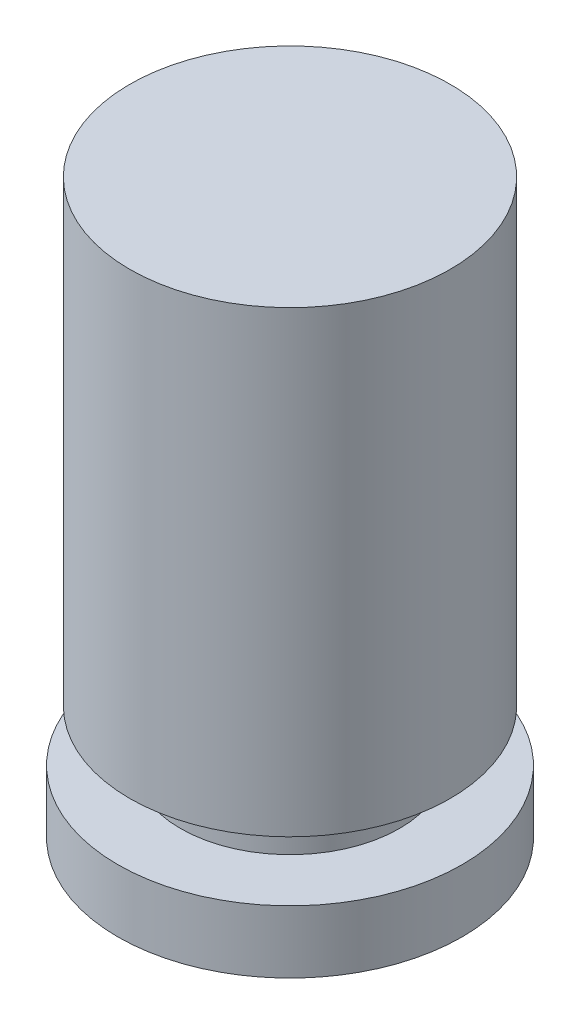
SolidWorks part; units mm, degrees
ref_plane "Front Plane" through (0, 0, 0) normal (0, 0, 1) x (1, 0, 0)
ref_plane "Top Plane" through (0, 0, 0) normal (0, 1, 0) x (1, 0, 0)
ref_plane "Right Plane" through (0, 0, 0) normal (1, 0, 0) x (0, 0, -1)
sketch "Sketch1" plane through (0, 0, 0) normal (0, 1, 0) x (1, 0, 0)
  circle A0 centre (0, 0) radius 34.925
extrude "Boss-Extrude1" add sketch "Sketch1" along normal blind 12.7
sketch "Sketch2" plane through (0, 12.7, 0) normal (0, 1, 0) x (1, 0, 0)
  circle A0 centre (0, 0) radius 22.225
extrude "Boss-Extrude2" add sketch "Sketch2" along normal blind 10.414
sketch "Sketch3" plane through (0, 23.114, 0) normal (0, 1, 0) x (1, 0, 0)
  circle A0 centre (0, 0) radius 32.512
extrude "Boss-Extrude3" add sketch "Sketch3" along normal blind 92.964
